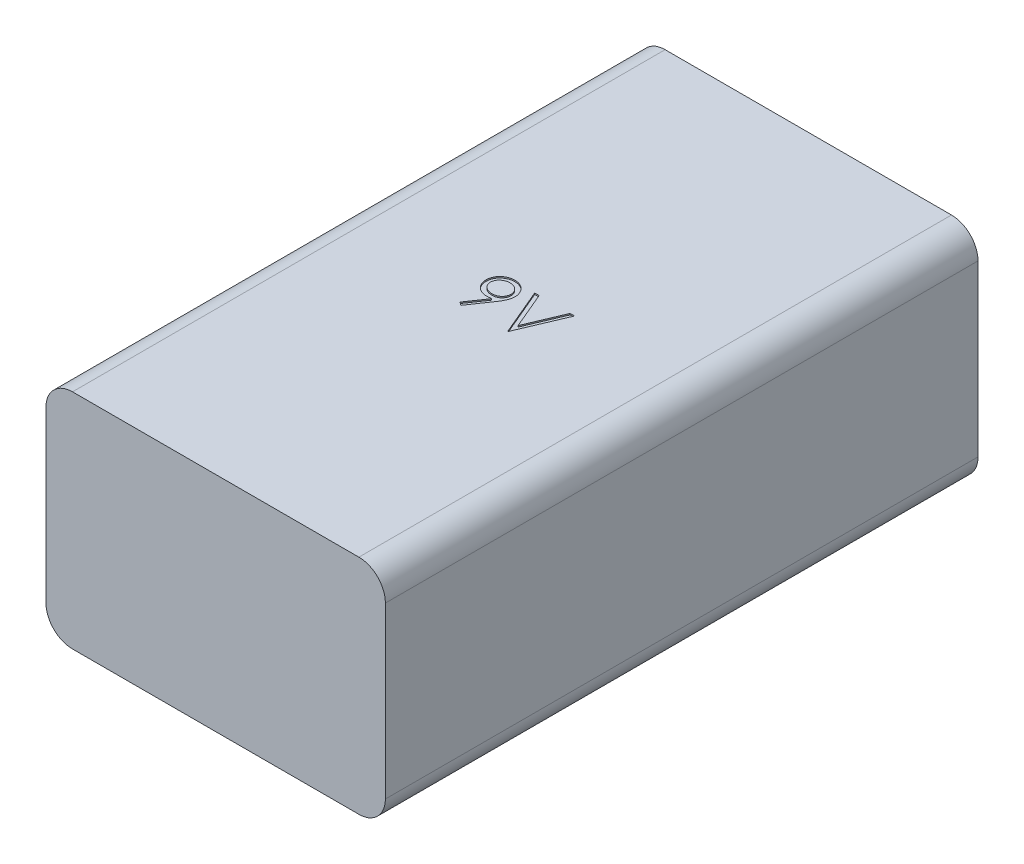
SolidWorks part; units mm, degrees
ref_plane "Front Plane" through (0, 0, 0) normal (0, 0, 1) x (1, 0, 0)
ref_plane "Top Plane" through (0, 0, 0) normal (0, 1, 0) x (1, 0, 0)
ref_plane "Right Plane" through (0, 0, 0) normal (1, 0, 0) x (0, 0, -1)
sketch "Sketch1" plane through (0, 0, 0) normal (0, 1, 0) x (1, 0, 0)
  line L1 (-24.3175, 42.4848) -> (1.2825, 42.4848)
  line L2 (-24.3175, 42.4848) -> (-24.3175, -2.2152)
  line L3 (-24.3175, -2.2152) -> (1.2825, -2.2152)
  line L4 (1.2825, 42.4848) -> (1.2825, -2.2152)
  dimension "D1" = 44.7
  dimension "D2" = 25.6
extrude "Boss-Extrude1" add sketch "Sketch1" along normal blind 16.8 contours L3 L4 L1 L2
fillet "Fillet1" radius 2 4 edges at (1.2825, 16.8, -20.1348) (-24.3175, 16.8, -20.1348) (-24.3175, 0, -20.1348) (1.2825, 0, -20.1348)
sketch "Sketch2" plane through (0, 0, -42.4848) normal (0, 0, -1) x (-1, 0, 0)
  line L0 (24.3175, 14.8) -> (24.3175, 2) construction
  line L1 (5.0675, 12.7301) -> (1.3175, 10.5651)
  line L2 (1.3175, 10.5651) -> (1.3175, 6.2349)
  line L3 (1.3175, 6.2349) -> (5.0675, 4.0699)
  line L4 (5.0675, 4.0699) -> (8.8175, 6.2349)
  line L5 (8.8175, 6.2349) -> (8.8175, 10.5651)
  line L6 (8.8175, 10.5651) -> (5.0675, 12.7301)
  line L7 (-1.2825, 14.8) -> (-1.2825, 2) construction
  circle A0 centre (17.7675, 8.4) radius 2.75
  circle A1 centre (5.0675, 8.4) radius 3.75 construction
  point P14 (-1.2825, 8.4)
  point P16 (24.3175, 8.4)
  dimension "D2" = 5.5
  dimension "D1" = 7.5
  dimension "D3" = 6.55
  dimension "D4" = 10.1
  dimension "D5" = 0
  dimension "D6" = 0
extrude "Boss-Extrude2" add sketch "Sketch2" along normal blind 47.3 from surface at -44.7 starting at face at (-11.5175, 8.4, 2.2152)
sketch "Sketch3" plane through (0, 16.8, 0) normal (0, 1, 0) x (1, 0, 0)
  line L0 (-22.3175, 20.1348) -> (-0.7175, 20.1348) construction
  line L1 (-22.3175, 42.4848) -> (-22.3175, -2.2152) construction
  line L2 (-0.7175, -2.2152) -> (-0.7175, 42.4848) construction
  line L3 (-11.5175, 42.4848) -> (-11.5175, -2.2152) construction
  line L4 (-22.3175, 42.4848) -> (-0.7175, 42.4848) construction
  line L5 (-22.3175, -2.2152) -> (-0.7175, -2.2152) construction
  text T0 "9V"
extrude "Cut-Extrude1" cut sketch "Sketch3" against normal blind 0.1
equation "\"D3@Sketch2\"=9.3 - (5.5/2)"
